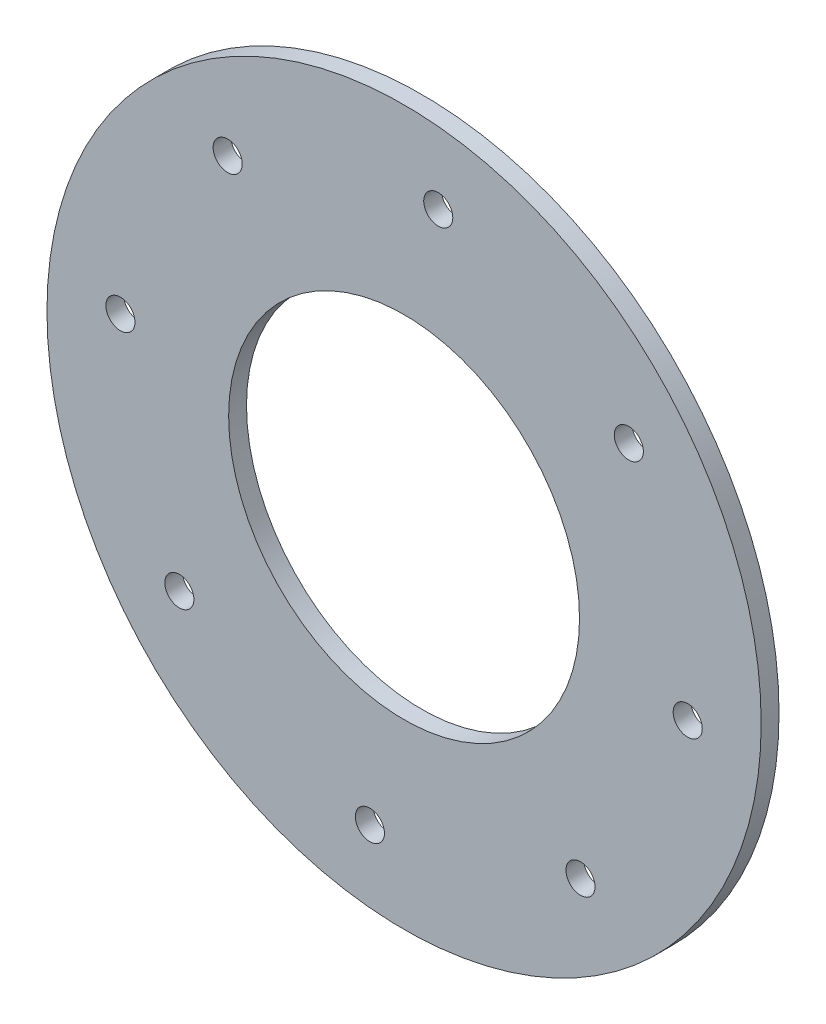
SolidWorks part; units mm, degrees
ref_plane "Front Plane" through (0, 0, 0) normal (0, 0, 1) x (1, 0, 0)
ref_plane "Top Plane" through (0, 0, 0) normal (0, 1, 0) x (1, 0, 0)
ref_plane "Right Plane" through (0, 0, 0) normal (1, 0, 0) x (0, 0, -1)
sketch "Sketch1" plane through (0, 0, 0) normal (0, 0, 1) x (1, 0, 0)
  circle A0 centre (0, 0) radius 29.4769
  circle A1 centre (0, 0) radius 60
  circle A2 centre (-29.6363, 37.7583) radius 2.4439
  circle A3 centre (5.7431, 47.6552) radius 2.4439
  circle A4 centre (37.7583, 29.6363) radius 2.4439
  circle A5 centre (47.6552, -5.7431) radius 2.4439
  circle A6 centre (29.6363, -37.7583) radius 2.4439
  circle A7 centre (-5.7431, -47.6552) radius 2.4439
  circle A8 centre (-37.7583, -29.6363) radius 2.4439
  circle A9 centre (-47.6552, 5.7431) radius 2.4439
  point P22 (0, 0)
  dimension "D1" = 48
  dimension "D3" = 120
  dimension "D2" = 8
extrude "Boss-Extrude1" add sketch "Sketch1" along normal blind 3
